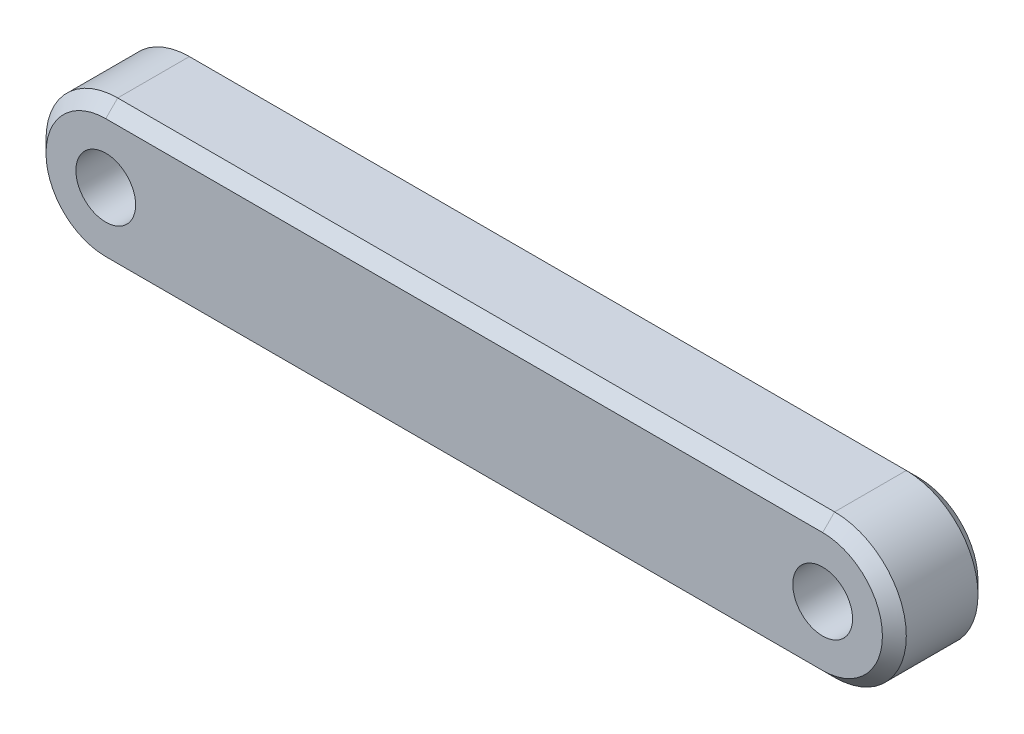
SolidWorks part; units mm, degrees
ref_plane "Alzado" through (0, 0, 0) normal (0, 0, 1) x (1, 0, 0)
ref_plane "Planta" through (0, 0, 0) normal (0, 1, 0) x (1, 0, 0)
ref_plane "Vista lateral" through (0, 0, 0) normal (1, 0, 0) x (0, 0, -1)
sketch "Croquis1" plane through (0, 0, 0) normal (0, 0, 1) x (1, 0, 0)
  line L0 (0, 0) -> (30, 0) construction
  line L1 (0, 3) -> (30, 3)
  line L2 (0, -3) -> (30, -3)
  arc A0 (0, 3) -> (0, -3) centre (0, 0) ccw
  arc A1 (30, -3) -> (30, 3) centre (30, 0) ccw
  circle A2 centre (30, 0) radius 1.25
  circle A3 centre (0, 0) radius 1.25
  point P3 (15, 0)
  dimension "D2" = 3
  dimension "D3" = 2.5
  dimension "D1" = 30
extrude "Saliente-Extruir1" add sketch "Croquis1" along normal blind 4
chamfer "Chaflán1" distance 0.5 angle 45 8 edges at (15, -3, 4) (33, 0, 4) (-3, 0, 4) (15, 3, 4) (15, -3, 0) (33, 0, 0) (-3, 0, 0) (15, 3, 0)
